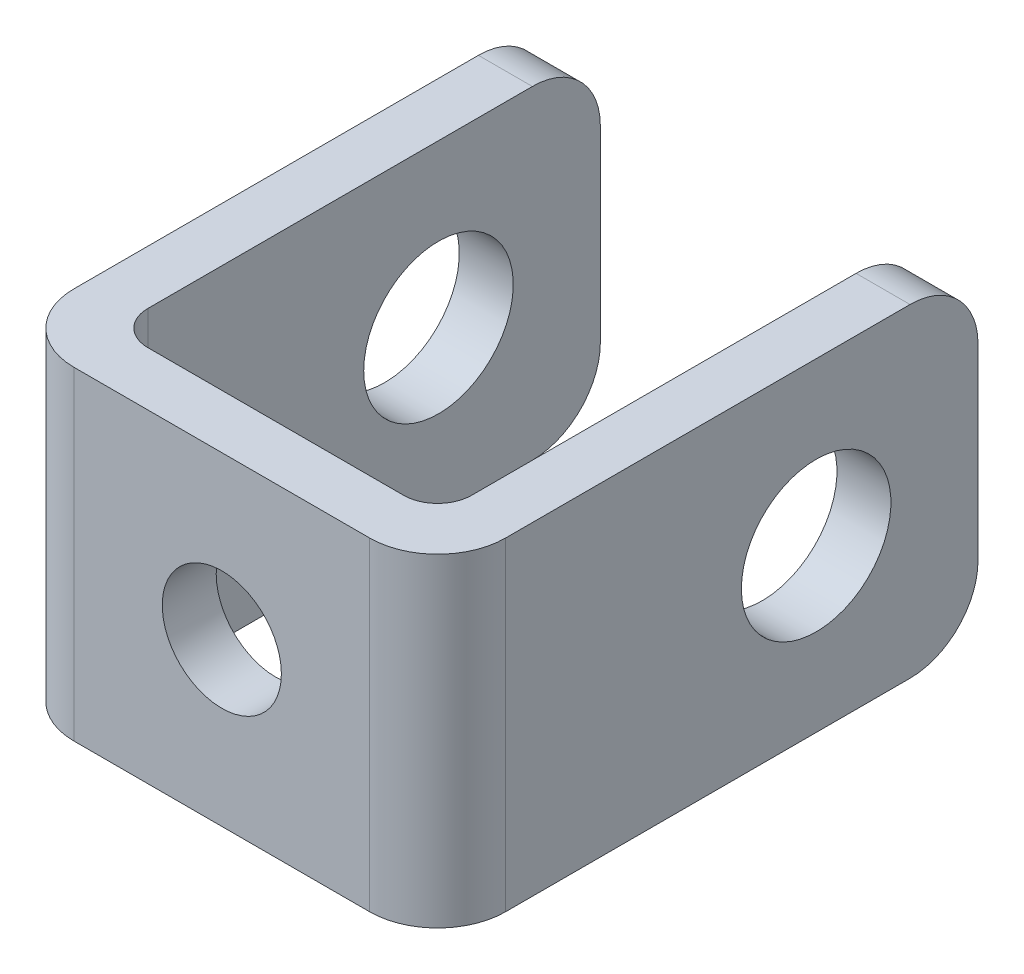
SolidWorks part; units mm, degrees
ref_plane "Front Plane" through (0, 0, 0) normal (0, 0, 1) x (1, 0, 0)
ref_plane "Top Plane" through (0, 0, 0) normal (0, 1, 0) x (1, 0, 0)
ref_plane "Right Plane" through (0, 0, 0) normal (1, 0, 0) x (0, 0, -1)
sketch "Sketch1" plane through (0, 0, 0) normal (0, 1, 0) x (1, 0, 0)
  line L0 (0, 0) -> (0, -15.9004)
  line L1 (0, -15.9004) -> (12.7, -15.9004)
  line L2 (12.7, -15.9004) -> (12.7, 0)
  point P3 (0, 0)
  dimension "D1" = 15.9004
  dimension "D2" = 12.7
extrude "Extrude-Thin1" add sketch "Sketch1" along normal blind 9.525 thin thin type one direction reverse wall 1.5875
fillet "Fillet1" radius 1 2 edges at (11.1125, 4.7625, 14.3129) (1.5875, 4.7625, 14.3129)
fillet "Fillet3" radius 2 2 edges at (12.7, 4.7625, 15.9004) (0, 4.7625, 15.9004)
fillet "Fillet4" radius 2 4 edges at (0.7937, 0, 0) (11.9062, 0, 0) (11.9062, 9.525, 0) (0.7937, 9.525, 0)
sketch "Sketch2" plane through (0, 0, 0) normal (-1, 0, 0) x (0, 0, 1)
  line L0 (0, 7.525) -> (0, 2) construction
  line L1 (2, 9.525) -> (13.9004, 9.525) construction
  circle A0 centre (4.7625, 4.7625) radius 2.2
  dimension "D3" = 4.4
  dimension "D1" = 4.7625
  dimension "D2" = 4.7625
extrude "Cut-Extrude1" cut sketch "Sketch2" against normal through all
sketch "Sketch3" plane through (0, 0, 15.9004) normal (0, 0, 1) x (1, 0, 0)
  line L0 (2, 9.525) -> (10.7, 0) construction
  circle A0 centre (6.35, 4.7625) radius 1.7525
  point P6 (6.35, 4.7625)
  point P7 (0, 0)
  point P8 (0, 0)
  dimension "D1" = 3.505
extrude "Cut-Extrude2" cut sketch "Sketch3" against normal up to next
